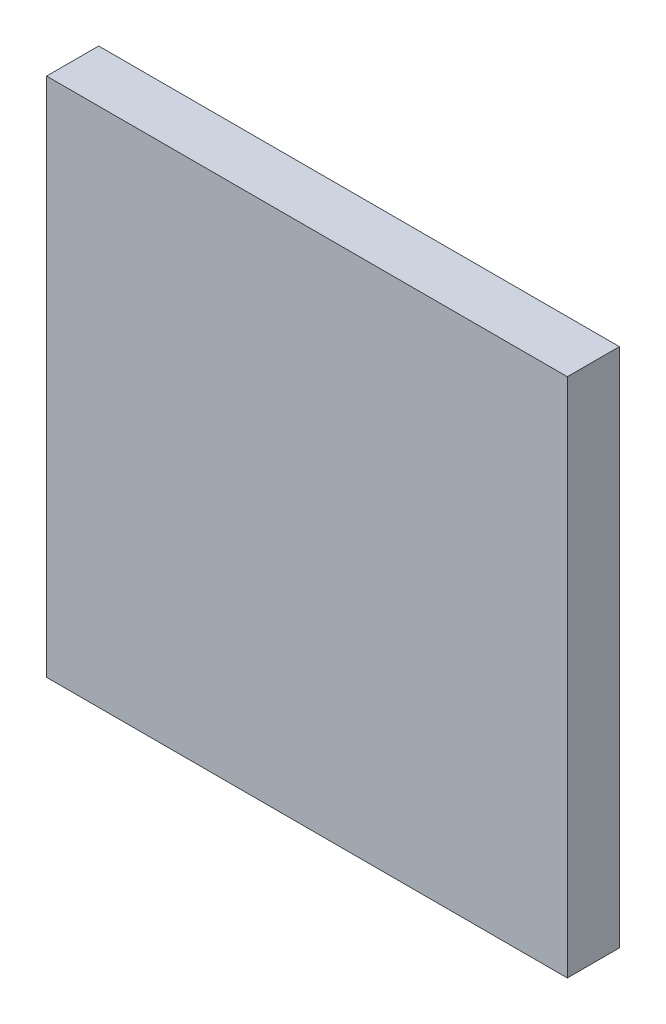
SolidWorks part; units mm, degrees
ref_plane "Front" through (0, 0, 0) normal (0, 0, 1) x (1, 0, 0)
ref_plane "Top" through (0, 0, 0) normal (0, 1, 0) x (1, 0, 0)
ref_plane "Right" through (0, 0, 0) normal (1, 0, 0) x (0, 0, -1)
other "Configuration Table"
sketch "Sketch1" plane through (0, 0, 0) normal (0, 0, 1) x (1, 0, 0)
  line L1 (0, 0) -> (100, 0)
  line L2 (0, 0) -> (0, 100)
  line L3 (0, 100) -> (100, 100)
  line L4 (100, 0) -> (100, 100)
  dimension "D1" = 100
  dimension "D2" = 100
extrude "Extrude1" add sketch "Sketch1" along normal blind 10
